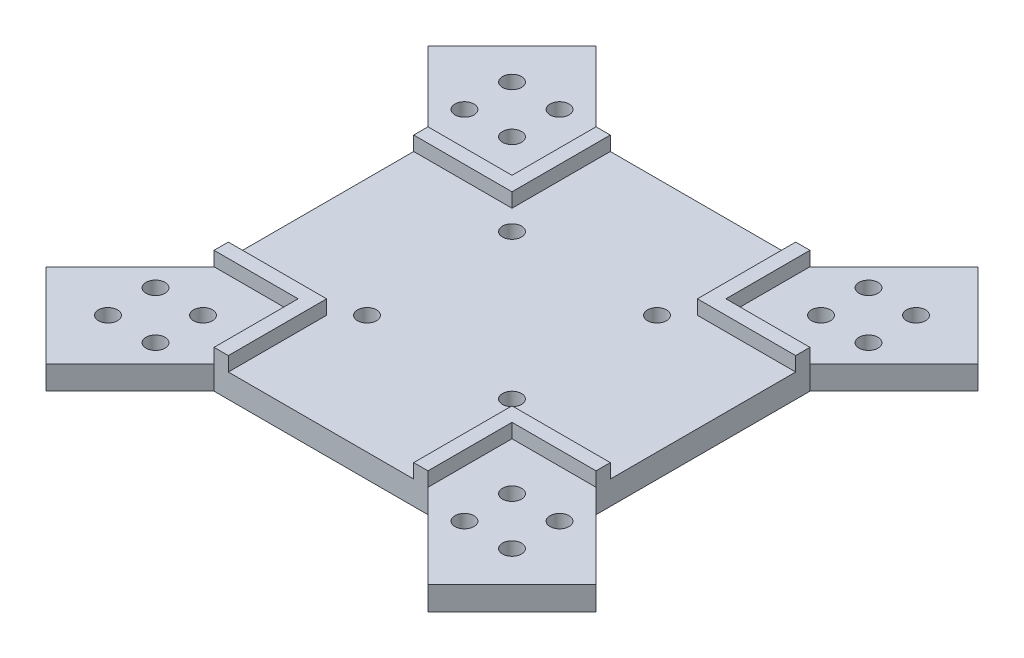
SolidWorks part; units mm, degrees
ref_plane "정면" through (0, 0, 0) normal (0, 0, 1) x (1, 0, 0)
ref_plane "윗면" through (0, 0, 0) normal (0, 1, 0) x (1, 0, 0)
ref_plane "우측면" through (0, 0, 0) normal (1, 0, 0) x (0, 0, -1)
sketch "스케치1" plane through (0, 0, 0) normal (0, 1, 0) x (1, 0, 0)
  line L0 (-22.5, 40.1777) -> (22.5, -40.1777) construction
  line L1 (-22.5, 40.1777) -> (22.5, 40.1777)
  line L2 (-40.1777, 22.5) -> (-40.1777, -22.5)
  line L3 (-22.5, -40.1777) -> (22.5, -40.1777)
  line L4 (40.1777, 22.5) -> (40.1777, -22.5)
  line L5 (57.8553, 40.1777) -> (40.1777, 22.5)
  line L6 (-22.5, 40.1777) -> (-40.1777, 22.5)
  line L7 (-22.5, 40.1777) -> (-40.1777, 57.8553)
  line L8 (-40.1777, 57.8553) -> (-57.8553, 40.1777)
  line L9 (-40.1777, 22.5) -> (-57.8553, 40.1777)
  line L14 (57.8553, 40.1777) -> (40.1777, 57.8553)
  line L15 (40.1777, 57.8553) -> (22.5, 40.1777)
  line L16 (40.1777, 22.5) -> (22.5, 40.1777)
  line L17 (57.8553, -40.1777) -> (40.1777, -57.8553)
  line L18 (57.8553, -40.1777) -> (40.1777, -22.5)
  line L19 (40.1777, -22.5) -> (22.5, -40.1777)
  line L20 (40.1777, -57.8553) -> (22.5, -40.1777)
  line L21 (-22.5, -40.1777) -> (-40.1777, -57.8553)
  line L22 (-22.5, -40.1777) -> (-40.1777, -22.5)
  line L23 (-40.1777, -22.5) -> (-57.8553, -40.1777)
  line L24 (-40.1777, -57.8553) -> (-57.8553, -40.1777)
  dimension "D1" = 45
  dimension "D2" = 45
  dimension "D3" = 25
  dimension "D4" = 25
  dimension "D5" = 25
  dimension "D6" = 25
  dimension "D7" = 135
extrude "보스-돌출1" add sketch "스케치1" along normal blind 5 contours L9 L6 L7 L8 | L0 L6 L2 L22 L3 | L24 L21 L22 L23 | L1 L0 L19 L4 L16 | L20 L17 L18 L19 | L16 L5 L14 L15
sketch "스케치2" plane through (0, 5, 0) normal (0, 1, 0) x (1, 0, 0)
  line L1 (-40.1777, -19.5) -> (-22.5, -19.5)
  line L2 (-40.1777, -19.5) -> (-40.1777, -22.5)
  line L3 (-40.1777, -22.5) -> (-22.5, -22.5)
  line L4 (-22.5, -19.5) -> (-22.5, -22.5)
  line L5 (-22.5, -19.5) -> (-19.5, -19.5)
  line L6 (-22.5, -19.5) -> (-22.5, -40.1777)
  line L7 (-22.5, -40.1777) -> (-19.5, -40.1777)
  line L8 (-19.5, -19.5) -> (-19.5, -40.1777)
  line L128 (-19.5, 40.1777) -> (-19.5, 22.5)
  line L129 (-19.5, 40.1777) -> (-22.5, 40.1777)
  line L130 (-19.5, 22.5) -> (-22.5, 22.5)
  line L131 (-22.5, 40.1777) -> (-22.5, 22.5)
  line L132 (-19.5, 22.5) -> (-40.1777, 22.5)
  line L133 (-19.5, 22.5) -> (-19.5, 19.5)
  line L134 (-19.5, 19.5) -> (-40.1777, 19.5)
  line L135 (-40.1777, 22.5) -> (-40.1777, 19.5)
  line L136 (40.1777, 19.5) -> (22.5, 19.5)
  line L137 (40.1777, 19.5) -> (40.1777, 22.5)
  line L138 (22.5, 19.5) -> (22.5, 22.5)
  line L139 (40.1777, 22.5) -> (22.5, 22.5)
  line L140 (22.5, 19.5) -> (22.5, 40.1777)
  line L141 (22.5, 19.5) -> (19.5, 19.5)
  line L142 (19.5, 19.5) -> (19.5, 40.1777)
  line L143 (22.5, 40.1777) -> (19.5, 40.1777)
  line L144 (19.5, -40.1777) -> (19.5, -22.5)
  line L145 (19.5, -40.1777) -> (22.5, -40.1777)
  line L146 (19.5, -22.5) -> (22.5, -22.5)
  line L147 (22.5, -40.1777) -> (22.5, -22.5)
  line L148 (19.5, -22.5) -> (40.1777, -22.5)
  line L149 (19.5, -22.5) -> (19.5, -19.5)
  line L150 (19.5, -19.5) -> (40.1777, -19.5)
  line L151 (40.1777, -22.5) -> (40.1777, -19.5)
  point P4 (0, 0)
  point P37 (0, 0)
  line M10 (-40.1777, 22.5) -> (-40.1777, -22.5)
  line M14 (-22.5, -40.1777) -> (22.5, -40.1777)
  dimension "D1" = 3
  dimension "D2" = 4
extrude "보스-돌출2" add sketch "스케치2" along normal blind 3 contours L4 L1 L3 M10 | L8 L5 L4 L6 M14
sketch "스케치4" plane through (0, 0, 0) normal (0, 1, 0) x (1, 0, 0)
  line L0 (-32.5, -32.5) -> (-32.5, -22.5) construction
  line L1 (-40.1777, -22.5) -> (-22.5, -22.5) construction
  line L2 (-42.5, -42.5) -> (-32.5, -42.5) construction
  line L3 (-32.5, -42.5) -> (-32.5, -32.5) construction
  line L4 (-32.5, -32.5) -> (-42.5, -32.5) construction
  line L5 (-40.1777, -22.5) -> (-22.5, -22.5) construction
  line L6 (-22.5, -22.5) -> (-22.5, -40.1777) construction
  line L7 (-22.5, -22.5) -> (-22.5, -40.1777) construction
  line L8 (-32.5, -32.5) -> (-22.5, -32.5) construction
  circle A0 centre (-42.5, -42.5) radius 2
  circle A1 centre (-32.5, -42.5) radius 2
  circle A2 centre (-42.5, -32.5) radius 2
  circle A3 centre (-32.5, -32.5) radius 2
  circle A4 centre (-32.5, 32.5) radius 2
  circle A5 centre (-42.5, 32.5) radius 2
  circle A6 centre (-42.5, 42.5) radius 2
  circle A7 centre (-32.5, 42.5) radius 2
  circle A8 centre (32.5, 32.5) radius 2
  circle A9 centre (32.5, 42.5) radius 2
  circle A10 centre (42.5, 42.5) radius 2
  circle A11 centre (42.5, 32.5) radius 2
  circle A12 centre (32.5, -32.5) radius 2
  circle A13 centre (42.5, -32.5) radius 2
  circle A14 centre (42.5, -42.5) radius 2
  circle A15 centre (32.5, -42.5) radius 2
  point P2 (-39.3814, 25.4685)
  point P29 (0, 0)
  point P38 (0, 0)
  dimension "D1" = 4
  dimension "D2" = 10
  dimension "D3" = 10
  dimension "D4" = 4
extrude "컷-돌출1" cut sketch "스케치4" along normal blind 5
sketch "스케치6" plane through (0, 0, 0) normal (0, 1, 0) x (1, 0, 0)
  line L0 (-15.25, 15.25) -> (-15.25, -15.25) construction
  line L1 (-15.25, -15.25) -> (15.25, -15.25) construction
  line L2 (15.25, -15.25) -> (15.25, 15.25) construction
  line L3 (-15.25, 15.25) -> (15.25, -15.25) construction
  circle A0 centre (-15.25, 15.25) radius 2
  circle A1 centre (15.25, -15.25) radius 2
  circle A2 centre (15.25, 15.25) radius 2
  circle A3 centre (-15.25, -15.25) radius 2
  point P2 (-15.25, 15.25)
  dimension "D1" = 4
  dimension "D2" = 30.5
extrude "컷-돌출2" cut sketch "스케치6" along normal blind 5
